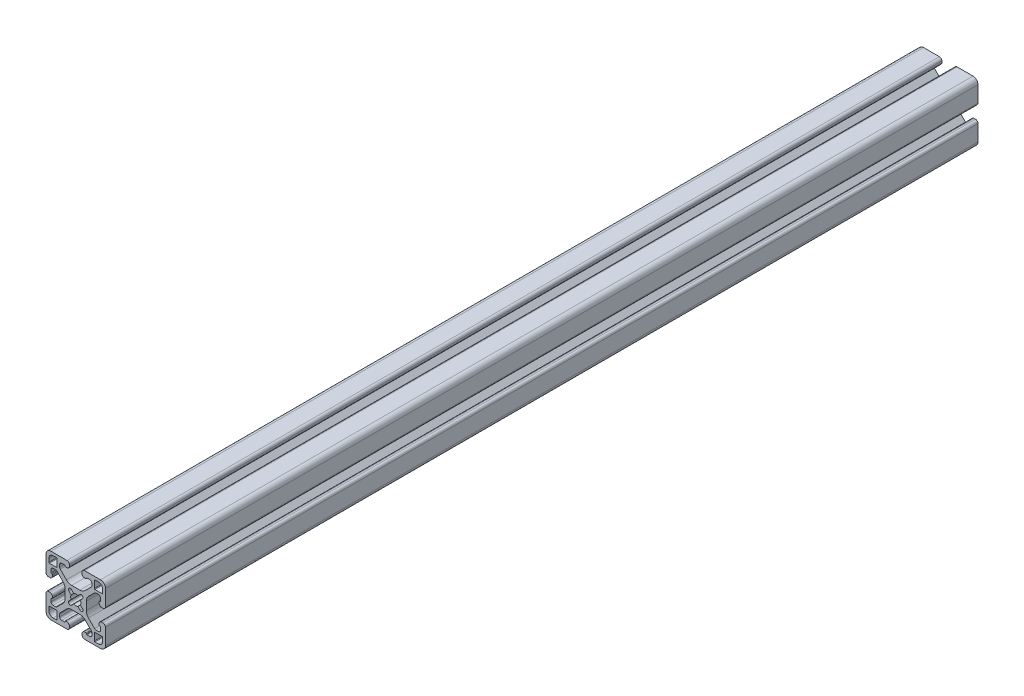
SolidWorks part; units mm, degrees
ref_plane "Front Plane" through (0, 0, 0) normal (0, 0, 1) x (1, 0, 0)
ref_plane "Top Plane" through (0, 0, 0) normal (0, 1, 0) x (1, 0, 0)
ref_plane "Right Plane" through (0, 0, 0) normal (1, 0, 0) x (0, 0, -1)
sketch "Sketch1" plane through (0, 0, 0) normal (0, 0, 1) x (1, 0, 0)
  line L0 (-66.7042, -2.4885) -> (-65.3338, -1.1181)
  line L1 (-65.3338, 1.5948) -> (-66.7042, 2.9652)
  line L2 (-65.0878, 4.5817) -> (-63.7174, 3.2113)
  line L3 (-61.0045, 3.2113) -> (-59.7212, 4.484)
  line L4 (-58.1153, 2.8781) -> (-59.3881, 1.5948)
  line L5 (-59.3881, -1.1181) -> (-58.0176, -2.4885)
  line L6 (-59.6341, -4.1049) -> (-61.0045, -2.7345)
  line L7 (-63.7174, -2.7345) -> (-65.0878, -4.1049)
  line L8 (-79.6075, 12.4812) -> (-79.6075, 14.691)
  line L9 (-76.8135, 17.485) -> (-74.6037, 17.485)
  line L10 (-74.2227, 17.104) -> (-74.2227, 12.4812)
  line L11 (-74.6037, 12.1002) -> (-79.2265, 12.1002)
  line L12 (-74.6037, -17.0082) -> (-76.8135, -17.0082)
  line L13 (-79.6075, -14.2142) -> (-79.6075, -12.0044)
  line L14 (-79.2265, -11.6234) -> (-74.6037, -11.6234)
  line L15 (-74.2227, -12.0044) -> (-74.2227, -16.6272)
  line L16 (-45.1143, -12.0044) -> (-45.1143, -14.2142)
  line L17 (-47.9083, -17.0082) -> (-50.1181, -17.0082)
  line L18 (-50.4991, -16.6272) -> (-50.4991, -12.0044)
  line L19 (-50.1181, -11.6234) -> (-45.4953, -11.6234)
  line L20 (-50.1181, 17.485) -> (-47.9083, 17.485)
  line L21 (-45.1143, 14.691) -> (-45.1143, 12.4812)
  line L22 (-45.4953, 12.1002) -> (-50.1181, 12.1002)
  line L23 (-50.4991, 12.4812) -> (-50.4991, 17.104)
  line L24 (-46.5368, -7.0006) -> (-46.5368, -8.7746)
  line L25 (-47.8067, -10.0486) -> (-49.3926, -10.0486)
  line L26 (-50.2907, -9.6767) -> (-54.2388, -5.7286)
  line L27 (-55.6299, -2.3699) -> (-55.6299, 2.8467)
  line L28 (-54.2388, 6.2053) -> (-50.2907, 10.1534)
  line L29 (-49.3926, 10.5254) -> (-47.8067, 10.5254)
  line L30 (-46.5368, 9.2513) -> (-46.5368, 7.4774)
  line L31 (-46.9178, 7.0964) -> (-46.994, 7.0964)
  line L32 (-47.375, 6.7154) -> (-47.3749, 5.8772)
  line L33 (-45.8001, 4.3024) -> (-44.8857, 4.3024)
  line L34 (-43.3109, 5.8772) -> (-43.3109, 16.1134)
  line L35 (-46.4859, 19.2884) -> (-56.7221, 19.2884)
  line L36 (-58.2969, 17.7136) -> (-58.2969, 16.7992)
  line L37 (-56.7222, 15.2244) -> (-55.884, 15.2244)
  line L38 (-55.503, 15.6054) -> (-55.503, 15.6816)
  line L39 (-55.122, 16.0626) -> (-53.348, 16.0626)
  line L40 (-52.0739, 14.7926) -> (-52.0739, 13.2067)
  line L41 (-52.4459, 12.3087) -> (-56.394, 8.3606)
  line L42 (-59.7526, 6.9694) -> (-64.9693, 6.9694)
  line L43 (-68.3279, 8.3606) -> (-72.276, 12.3087)
  line L44 (-72.6479, 13.2067) -> (-72.6479, 14.7926)
  line L45 (-71.3739, 16.0626) -> (-69.5999, 16.0626)
  line L46 (-69.2189, 15.6816) -> (-69.2189, 15.6054)
  line L47 (-68.8379, 15.2244) -> (-67.9997, 15.2244)
  line L48 (-66.4249, 16.7992) -> (-66.4249, 17.7136)
  line L49 (-67.9997, 19.2884) -> (-78.2359, 19.2884)
  line L50 (-81.4109, 16.1134) -> (-81.4109, 5.8772)
  line L51 (-79.8361, 4.3024) -> (-78.9217, 4.3024)
  line L52 (-77.3469, 5.8772) -> (-77.3469, 6.7154)
  line L53 (-77.7279, 7.0964) -> (-77.8041, 7.0964)
  line L54 (-78.1851, 7.4774) -> (-78.1851, 9.2513)
  line L55 (-76.9151, 10.5254) -> (-75.3293, 10.5254)
  line L56 (-74.4312, 10.1534) -> (-70.4831, 6.2053)
  line L57 (-69.0919, 2.8467) -> (-69.0919, -2.3699)
  line L58 (-70.4831, -5.7286) -> (-74.4312, -9.6767)
  line L59 (-75.3293, -10.0486) -> (-76.9151, -10.0486)
  line L60 (-78.1851, -8.7746) -> (-78.1851, -7.0006)
  line L61 (-77.8041, -6.6196) -> (-77.7279, -6.6196)
  line L62 (-77.3469, -6.2386) -> (-77.3469, -5.4004)
  line L63 (-78.9217, -3.8256) -> (-79.8361, -3.8256)
  line L64 (-81.4109, -5.4004) -> (-81.4109, -15.6366)
  line L65 (-78.2359, -18.8116) -> (-67.9997, -18.8116)
  line L66 (-66.4249, -17.2368) -> (-66.4249, -16.3224)
  line L67 (-67.9997, -14.7476) -> (-68.8379, -14.7476)
  line L68 (-69.2189, -15.1286) -> (-69.2189, -15.2048)
  line L69 (-69.5999, -15.5858) -> (-71.3739, -15.5858)
  line L70 (-72.6479, -14.3158) -> (-72.6479, -12.7299)
  line L71 (-72.276, -11.8319) -> (-68.3279, -7.8838)
  line L72 (-64.9693, -6.4926) -> (-59.7526, -6.4926)
  line L73 (-56.394, -7.8838) -> (-52.4459, -11.8319)
  line L74 (-52.0739, -12.7299) -> (-52.0739, -14.3158)
  line L75 (-53.348, -15.5858) -> (-55.122, -15.5858)
  line L76 (-55.503, -15.2048) -> (-55.503, -15.1286)
  line L77 (-55.884, -14.7476) -> (-56.7222, -14.7476)
  line L78 (-58.2969, -16.3224) -> (-58.2969, -17.2368)
  line L79 (-56.7221, -18.8116) -> (-46.4859, -18.8116)
  line L80 (-43.3109, -15.6366) -> (-43.3109, -5.4004)
  line L81 (-44.8857, -3.8256) -> (-45.8001, -3.8256)
  line L82 (-47.3749, -5.4004) -> (-47.375, -6.2386)
  line L83 (-46.994, -6.6196) -> (-46.9178, -6.6196)
  arc A0 (-66.7042, -2.4885) -> (-65.0878, -4.1049) centre (-65.896, -3.2967) ccw
  arc A1 (-65.3338, 1.5948) -> (-65.3338, -1.1181) centre (-62.3609, 0.2384) ccw
  arc A2 (-65.0878, 4.5817) -> (-66.7042, 2.9652) centre (-65.896, 3.7734) ccw
  arc A3 (-61.0045, 3.2113) -> (-63.7174, 3.2113) centre (-62.3609, 0.2384) ccw
  arc A4 (-58.1153, 2.8781) -> (-59.7212, 4.484) centre (-58.8259, 3.7734) ccw
  arc A5 (-59.3881, -1.1181) -> (-59.3881, 1.5948) centre (-62.3609, 0.2384) ccw
  arc A6 (-59.6341, -4.1049) -> (-58.0176, -2.4885) centre (-58.8259, -3.2967) ccw
  arc A7 (-63.7174, -2.7345) -> (-61.0045, -2.7345) centre (-62.3609, 0.2384) ccw
  arc A8 (-79.6075, 12.4812) -> (-79.2265, 12.1002) centre (-79.2265, 12.4812) ccw
  arc A9 (-76.8135, 17.485) -> (-79.6075, 14.691) centre (-76.8135, 14.691) ccw
  arc A10 (-74.2227, 17.104) -> (-74.6037, 17.485) centre (-74.6037, 17.104) ccw
  arc A11 (-74.6037, 12.1002) -> (-74.2227, 12.4812) centre (-74.6037, 12.4812) ccw
  arc A12 (-74.6037, -17.0082) -> (-74.2227, -16.6272) centre (-74.6037, -16.6272) ccw
  arc A13 (-79.6075, -14.2142) -> (-76.8135, -17.0082) centre (-76.8135, -14.2142) ccw
  arc A14 (-79.2265, -11.6234) -> (-79.6075, -12.0044) centre (-79.2265, -12.0044) ccw
  arc A15 (-74.2227, -12.0044) -> (-74.6037, -11.6234) centre (-74.6037, -12.0044) ccw
  arc A16 (-45.1143, -12.0044) -> (-45.4953, -11.6234) centre (-45.4953, -12.0044) ccw
  arc A17 (-47.9083, -17.0082) -> (-45.1143, -14.2142) centre (-47.9083, -14.2142) ccw
  arc A18 (-50.4991, -16.6272) -> (-50.1181, -17.0082) centre (-50.1181, -16.6272) ccw
  arc A19 (-50.1181, -11.6234) -> (-50.4991, -12.0044) centre (-50.1181, -12.0044) ccw
  arc A20 (-50.1181, 17.485) -> (-50.4991, 17.104) centre (-50.1181, 17.104) ccw
  arc A21 (-45.1143, 14.691) -> (-47.9083, 17.485) centre (-47.9083, 14.691) ccw
  arc A22 (-45.4953, 12.1002) -> (-45.1143, 12.4812) centre (-45.4953, 12.4812) ccw
  arc A23 (-50.4991, 12.4812) -> (-50.1181, 12.1002) centre (-50.1181, 12.4812) ccw
  arc A24 (-47.8067, -10.0486) -> (-46.5368, -8.7746) centre (-47.8067, -8.7786) ccw
  arc A25 (-50.2907, -9.6767) -> (-49.3926, -10.0486) centre (-49.3926, -8.7786) ccw
  arc A26 (-55.6299, -2.3699) -> (-54.2388, -5.7286) centre (-50.8801, -2.3699) ccw
  arc A27 (-54.2388, 6.2053) -> (-55.6299, 2.8467) centre (-50.8801, 2.8467) ccw
  arc A28 (-49.3926, 10.5254) -> (-50.2907, 10.1534) centre (-49.3926, 9.2554) ccw
  arc A29 (-46.5368, 9.2513) -> (-47.8067, 10.5254) centre (-47.8067, 9.2554) ccw
  arc A30 (-46.9178, 7.0964) -> (-46.5368, 7.4774) centre (-46.9178, 7.4774) ccw
  arc A31 (-46.994, 7.0964) -> (-47.375, 6.7154) centre (-46.994, 6.7154) ccw
  arc A32 (-47.3749, 5.8772) -> (-45.8001, 4.3024) centre (-45.8001, 5.8772) ccw
  arc A33 (-44.8857, 4.3024) -> (-43.3109, 5.8772) centre (-44.8857, 5.8772) ccw
  arc A34 (-43.3109, 16.1134) -> (-46.4859, 19.2884) centre (-46.4859, 16.1134) ccw
  arc A35 (-56.7221, 19.2884) -> (-58.2969, 17.7136) centre (-56.7221, 17.7136) ccw
  arc A36 (-58.2969, 16.7992) -> (-56.7222, 15.2244) centre (-56.7221, 16.7992) ccw
  arc A37 (-55.884, 15.2244) -> (-55.503, 15.6054) centre (-55.884, 15.6054) ccw
  arc A38 (-55.122, 16.0626) -> (-55.503, 15.6816) centre (-55.122, 15.6816) ccw
  arc A39 (-52.0739, 14.7926) -> (-53.348, 16.0626) centre (-53.3439, 14.7926) ccw
  arc A40 (-52.4459, 12.3087) -> (-52.0739, 13.2067) centre (-53.3439, 13.2067) ccw
  arc A41 (-59.7526, 6.9694) -> (-56.394, 8.3606) centre (-59.7526, 11.7192) ccw
  arc A42 (-68.3279, 8.3606) -> (-64.9693, 6.9694) centre (-64.9693, 11.7192) ccw
  arc A43 (-72.6479, 13.2067) -> (-72.276, 12.3087) centre (-71.3779, 13.2067) ccw
  arc A44 (-71.3739, 16.0626) -> (-72.6479, 14.7926) centre (-71.3779, 14.7926) ccw
  arc A45 (-69.2189, 15.6816) -> (-69.5999, 16.0626) centre (-69.5999, 15.6816) ccw
  arc A46 (-69.2189, 15.6054) -> (-68.8379, 15.2244) centre (-68.8379, 15.6054) ccw
  arc A47 (-67.9997, 15.2244) -> (-66.4249, 16.7992) centre (-67.9997, 16.7992) ccw
  arc A48 (-66.4249, 17.7136) -> (-67.9997, 19.2884) centre (-67.9997, 17.7136) ccw
  arc A49 (-78.2359, 19.2884) -> (-81.4109, 16.1134) centre (-78.2359, 16.1134) ccw
  arc A50 (-81.4109, 5.8772) -> (-79.8361, 4.3024) centre (-79.8361, 5.8772) ccw
  arc A51 (-78.9217, 4.3024) -> (-77.3469, 5.8772) centre (-78.9217, 5.8772) ccw
  arc A52 (-77.3469, 6.7154) -> (-77.7279, 7.0964) centre (-77.7279, 6.7154) ccw
  arc A53 (-78.1851, 7.4774) -> (-77.8041, 7.0964) centre (-77.8041, 7.4774) ccw
  arc A54 (-76.9151, 10.5254) -> (-78.1851, 9.2513) centre (-76.9151, 9.2554) ccw
  arc A55 (-74.4312, 10.1534) -> (-75.3293, 10.5254) centre (-75.3293, 9.2554) ccw
  arc A56 (-69.0919, 2.8467) -> (-70.4831, 6.2053) centre (-73.8417, 2.8467) ccw
  arc A57 (-70.4831, -5.7286) -> (-69.0919, -2.3699) centre (-73.8417, -2.3699) ccw
  arc A58 (-75.3293, -10.0486) -> (-74.4312, -9.6767) centre (-75.3293, -8.7786) ccw
  arc A59 (-78.1851, -8.7746) -> (-76.9151, -10.0486) centre (-76.9151, -8.7786) ccw
  arc A60 (-77.8041, -6.6196) -> (-78.1851, -7.0006) centre (-77.8041, -7.0006) ccw
  arc A61 (-77.7279, -6.6196) -> (-77.3469, -6.2386) centre (-77.7279, -6.2386) ccw
  arc A62 (-77.3469, -5.4004) -> (-78.9217, -3.8256) centre (-78.9217, -5.4004) ccw
  arc A63 (-79.8361, -3.8256) -> (-81.4109, -5.4004) centre (-79.8361, -5.4004) ccw
  arc A64 (-81.4109, -15.6366) -> (-78.2359, -18.8116) centre (-78.2359, -15.6366) ccw
  arc A65 (-67.9997, -18.8116) -> (-66.4249, -17.2368) centre (-67.9997, -17.2368) ccw
  arc A66 (-66.4249, -16.3224) -> (-67.9997, -14.7476) centre (-67.9997, -16.3224) ccw
  arc A67 (-68.8379, -14.7476) -> (-69.2189, -15.1286) centre (-68.8379, -15.1286) ccw
  arc A68 (-69.5999, -15.5858) -> (-69.2189, -15.2048) centre (-69.5999, -15.2048) ccw
  arc A69 (-72.6479, -14.3158) -> (-71.3739, -15.5858) centre (-71.3779, -14.3158) ccw
  arc A70 (-72.276, -11.8319) -> (-72.6479, -12.7299) centre (-71.3779, -12.7299) ccw
  arc A71 (-64.9693, -6.4926) -> (-68.3279, -7.8838) centre (-64.9693, -11.2424) ccw
  arc A72 (-56.394, -7.8838) -> (-59.7526, -6.4926) centre (-59.7526, -11.2424) ccw
  arc A73 (-52.0739, -12.7299) -> (-52.4459, -11.8319) centre (-53.3439, -12.7299) ccw
  arc A74 (-53.348, -15.5858) -> (-52.0739, -14.3158) centre (-53.3439, -14.3158) ccw
  arc A75 (-55.503, -15.2048) -> (-55.122, -15.5858) centre (-55.122, -15.2048) ccw
  arc A76 (-55.503, -15.1286) -> (-55.884, -14.7476) centre (-55.884, -15.1286) ccw
  arc A77 (-56.7222, -14.7476) -> (-58.2969, -16.3224) centre (-56.7221, -16.3224) ccw
  arc A78 (-58.2969, -17.2368) -> (-56.7221, -18.8116) centre (-56.7221, -17.2368) ccw
  arc A79 (-46.4859, -18.8116) -> (-43.3109, -15.6366) centre (-46.4859, -15.6366) ccw
  arc A80 (-43.3109, -5.4004) -> (-44.8857, -3.8256) centre (-44.8857, -5.4004) ccw
  arc A81 (-45.8001, -3.8256) -> (-47.3749, -5.4004) centre (-45.8001, -5.4004) ccw
  arc A82 (-47.375, -6.2386) -> (-46.994, -6.6196) centre (-46.994, -6.2386) ccw
  arc A83 (-46.5368, -7.0006) -> (-46.9178, -6.6196) centre (-46.9178, -7.0006) ccw
extrude "Extrude1" add sketch "Sketch1" against normal blind 558.8
